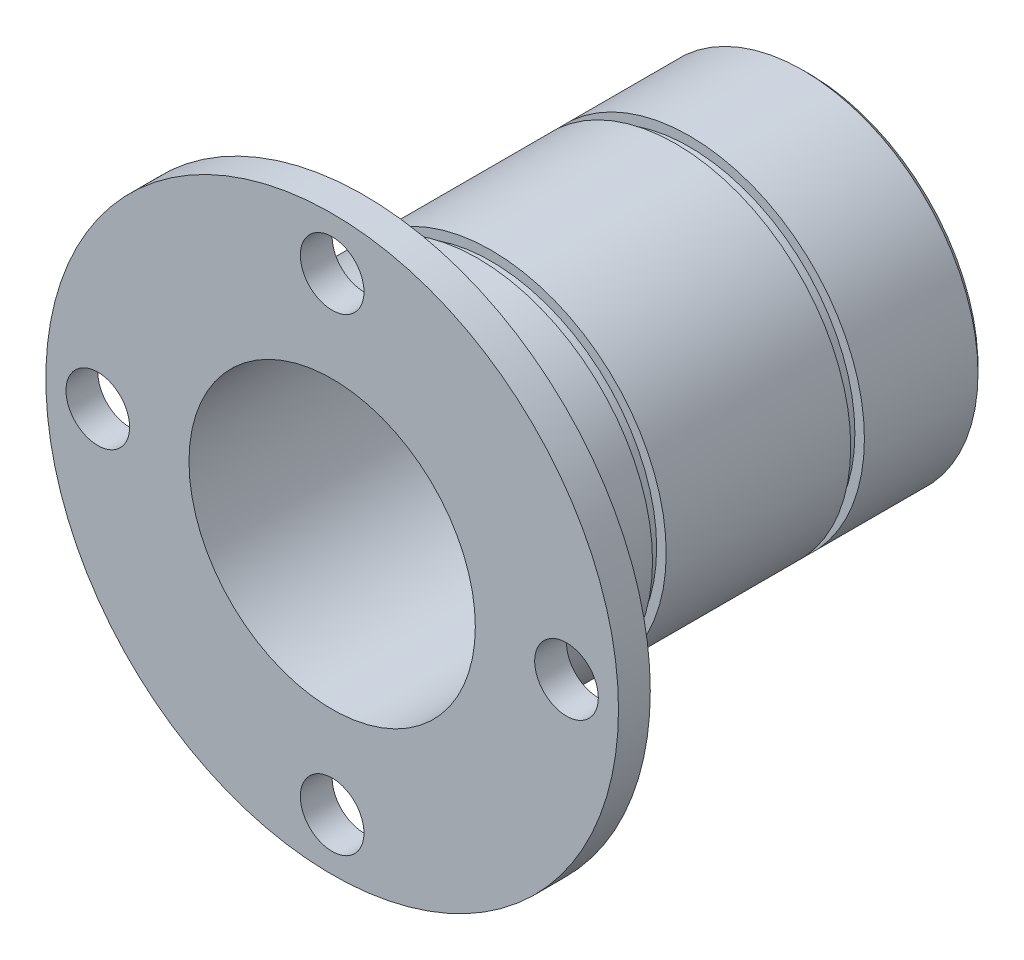
SolidWorks part; units mm, degrees
ref_plane "Płaszczyzna przednia" through (0, 0, 0) normal (0, 0, 1) x (1, 0, 0)
ref_plane "Płaszczyzna górna" through (0, 0, 0) normal (0, 1, 0) x (1, 0, 0)
ref_plane "Płaszczyzna prawa" through (0, 0, 0) normal (1, 0, 0) x (0, 0, -1)
sketch "Szkic1" plane through (0, 0, 0) normal (0, 0, 1) x (1, 0, 0)
  circle A0 centre (0, 0) radius 22.5
  circle A1 centre (0, 36.83) radius 5
  circle A2 centre (36.83, 0) radius 5
  circle A3 centre (0, -36.83) radius 5
  circle A4 centre (-36.83, 0) radius 5
  circle A5 centre (0, 0) radius 45
  point P14 (0, 0)
  dimension "D1" = 45
  dimension "D2" = 10
  dimension "D4" = 90
  dimension "D3" = 4
extrude "Dodanie-wyciągnięcie1" add sketch "Szkic1" along normal blind 5
sketch "Szkic2" plane through (0, 0, 0) normal (0, 0, -1) x (-1, 0, 0)
  circle A0 centre (0, 0) radius 22.5
  circle A1 centre (0, 0) radius 27.5
  dimension "D1" = 55
extrude "Dodanie-wyciągnięcie2" add sketch "Szkic2" along normal blind 70
sketch "Szkic3" plane through (0, 0, 0) normal (0, 1, 0) x (1, 0, 0)
  line L0 (0, 0) -> (0, 20)
  line L1 (26, 20) -> (27.5, 20)
  line L2 (27.5, 0) -> (27.5, 70) construction
  line L4 (27.5, 17.85) -> (26, 17.85)
  line L5 (26, 17.85) -> (26, 20)
  line L6 (27.5, 20) -> (28.3678, 20)
  line L7 (28.3678, 20) -> (28.3678, 17.85)
  line L8 (28.3678, 17.85) -> (27.5, 17.85)
  dimension "D1" = 20
  dimension "D2" = 2.15
  dimension "D3" = 1.5
revolve "Wycięcie-obrót1" cut sketch "Szkic3" angle 360 about L0
sketch "Szkic4" plane through (0, 0, 0) normal (0, 1, 0) x (1, 0, 0)
  line L0 (0, 0) -> (0, 10.0761)
  line L1 (27.5, 20) -> (27.5, 70) construction
  line L2 (27.5, 49) -> (26, 49)
  line L3 (26, 49) -> (26, 51.15)
  line L4 (26, 51.15) -> (28.7673, 51.15)
  line L5 (28.7673, 51.15) -> (28.7673, 49)
  line L6 (28.7673, 49) -> (27.5, 49)
  dimension "D2" = 1.5
  dimension "D3" = 2.15
revolve "Wycięcie-obrót2" cut sketch "Szkic4" angle 360 about L0
chamfer "Sfazowanie1" distance 1 angle 45 1 edges at (-27.5, 0, -70)
